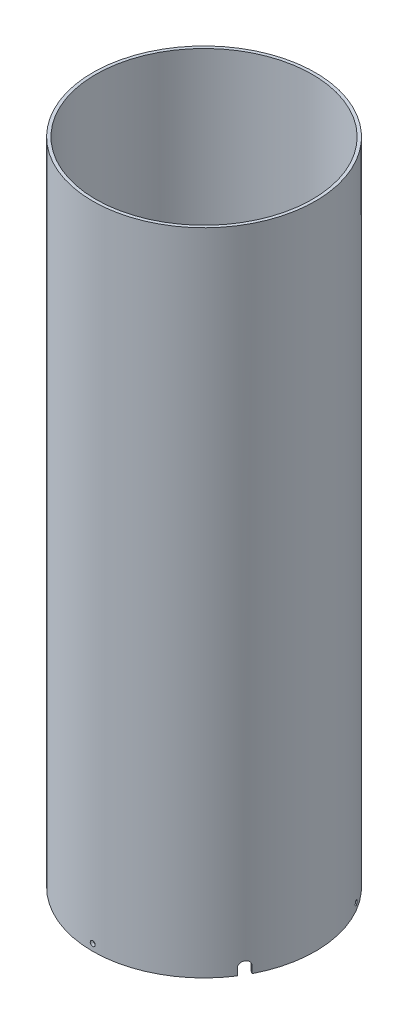
SolidWorks part; units mm, degrees
ref_plane "Front Plane" through (0, 0, 0) normal (0, 0, 1) x (1, 0, 0)
ref_plane "Top Plane" through (0, 0, 0) normal (0, 1, 0) x (1, 0, 0)
ref_plane "Right Plane" through (0, 0, 0) normal (1, 0, 0) x (0, 0, -1)
sketch "Sketch1" plane through (0, 0, 0) normal (0, 1, 0) x (1, 0, 0)
  circle A0 centre (0, 0) radius 76.2
  circle A1 centre (0, 0) radius 78.359
  dimension "D1" = 152.4
  dimension "D2" = 156.718
extrude "Boss-Extrude1" add sketch "Sketch1" along normal blind 457.2
ref_axis "Axis1" through (0, 457.2, 0) along (0, -1, 0)
sketch "Sketch2" plane through (0, 0, 0) normal (0, 0, 1) x (1, 0, 0)
  line L0 (0, 0) -> (0, 4.7625) construction
  circle A0 centre (0, 4.7625) radius 1.75
  dimension "D1" = 3.5
  dimension "D2" = 4.7625
extrude "Cut-Extrude1" cut sketch "Sketch2" against normal through all
pattern_circular "CirPattern1" count 6 over 360 about axis through (0, 457.2, 0) along (0, -1, 0) of "Cut-Extrude1"
ref_plane "Plane1" through (0, 0, -78.359) normal (0, 0, -1) x (-1, 0, 0)
sketch "Sketch3" plane through (0, 0, -78.359) normal (0, 0, -1) x (-1, 0, 0)
  line L0 (-3.81, 4.7329) -> (-3.81, 0)
  line L1 (-78.359, 0) -> (78.359, 0) construction
  line L2 (3.81, 4.7329) -> (3.81, 0)
  line L3 (-3.81, 0) -> (3.81, 0)
  arc A1 (3.81, 4.7329) -> (-3.81, 4.7329) centre (0, 4.7329) ccw
  point P0 (0, 4.7329)
  dimension "D1" = 7.62
extrude "Cut-Extrude2" cut sketch "Sketch3" against normal up to next
pattern_circular "CirPattern2" count 3 over 360 about axis through (0, 0, 0) along (0, 1, 0) of "Cut-Extrude2"
equation "\"D1@Boss-Extrude1\"=\"Aft_Upper_Length\""
equation "\"AB_Coupling_Section_Length\"= 0.375in"
equation "\"AB_Coupler_Num_Screws\"= 6"
equation "\"AB_Coupling_Screw_Diameter\"= 3.5mm"
equation "\"AB_Coupler_OD_Length\"= 2in"
equation "\"AB_Coupler_Length\"= \"AB_Coupler_OD_Length\" + \"AB_Coupling_Section_Length\" * 2"
equation "\"D1@Sketch2\"=\"AB_Coupling_Screw_Diameter\""
equation "\"D2@Sketch2\"=\"AB_Coupling_Section_Length\"/2"
equation "\"D1@CirPattern1\"=\"AB_Coupler_Num_Screws\""
equation "\"Aft_Section_Length\"= 40in"
equation "\"Aft_Upper_Length\"= \"Aft_Section_Length\" - \"Aft_Lower_Length\" - \"AB_Coupler_OD_Length\""
equation "\"Aft_Lower_Length\"= 20in"
